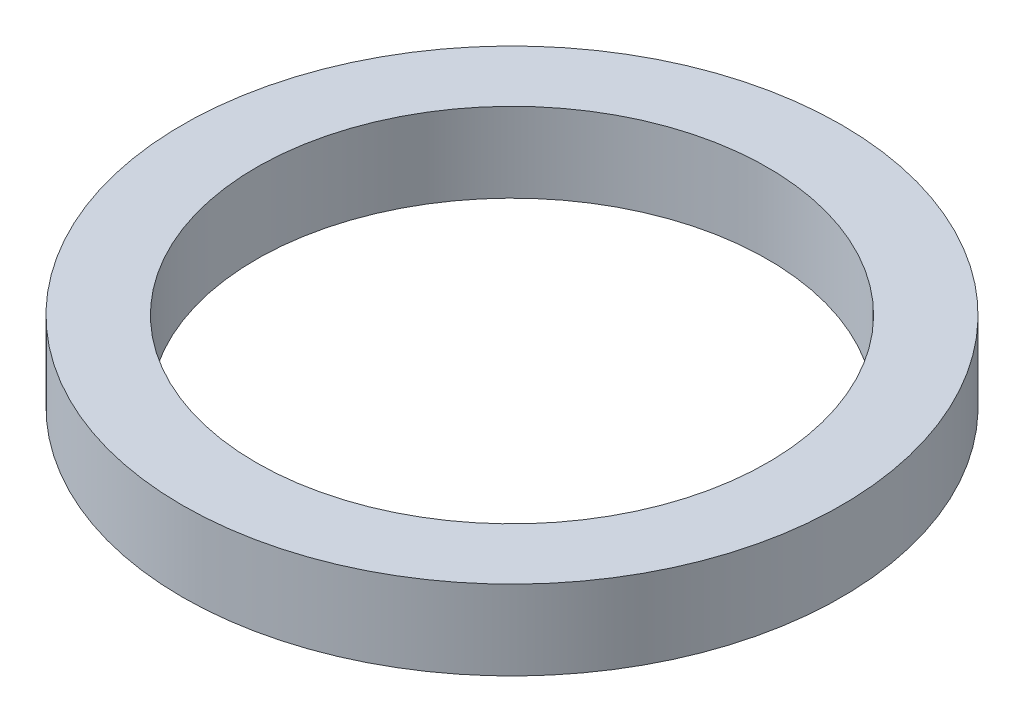
SolidWorks part; units mm, degrees
ref_plane "Front Plane" through (0, 0, 0) normal (0, 0, 1) x (1, 0, 0)
ref_plane "Top Plane" through (0, 0, 0) normal (0, 1, 0) x (1, 0, 0)
ref_plane "Right Plane" through (0, 0, 0) normal (1, 0, 0) x (0, 0, -1)
sketch "Sketch1" plane through (0, 0, 0) normal (0, 1, 0) x (1, 0, 0)
  circle A0 centre (0, 0) radius 22.5
  circle A1 centre (0, 0) radius 29
  dimension "D1" = 45
  dimension "D2" = 58
extrude "Boss-Extrude1" add sketch "Sketch1" along normal mid plane 7
equation "\"Nr\"= 78"
equation "\"module\"= 0.6"
equation "\"pressure_angle\"= 20.0"
equation "\"h_a\"= 0.6"
equation "\"h_f\"= 0.75"
equation "\"clr_tip_root\"= 0.15000000000000002"
equation "\"dp_r\"= 46.8"
equation "\"db_r\"= 43.97761465278051"
equation "\"fw_r\"= 22.845791438896047"
equation "\"alpha_r\"= 0.8539582918412556"
equation "\"beta_r\"= 4.015608891374819"
equation "\"bearing_ID\"= 45"
equation "\"bearing_OD\"= 58"
equation "\"bearing_height\"= 7"
equation "\"clearance_planet\"= 1.5"
equation "\"case_dist\"= 24.210783717444997"
equation "\"Motor_case_OD_max\"= 88.5"
equation "\"case_mounting_PCD\"= 81.0"
equation "\"bearing mount thickness\"= IIF((\"bearing_OD\" + \"output_mounting_hole_dia\" * 4) > (\"Nr\" * \"module\" + 2 * \"h_b\"), \"output_mounting_hole_dia\" * 2, ((\"Nr\" * \"module\" + 2 * \"h_b\" - (\"bearing_OD\" + \"output_mounting_hole_dia\" * 4)) / 2) + \"output_mounting_hole_dia\" * 2 + \"standard_clearance_1_5mm\")"
equation "\"case_mounting_hole_dia\"= 3"
equation "\"output_mounting_PCD\"= 66"
equation "\"output_mounting_hole_dia\"= 4"
equation "\"clearance_case_mount_holes_shell_thickness\"= 1"
equation "\"motor_case_OD_base\"= 79.0"
equation "\"sec_carrier_thickness\"= 5"
equation "\"sun_coupler_hub_thickness\"= 4"
equation "\"clearance_sun_coupler_sec_carrier\"= 1.5"
equation "\"clearance_motor_and_case\"= 5"
equation "\"motor_OD\"= 64"
equation "\"Motor_case_thickness\"= 2.5"
equation "\"Motor_case_ID\"= 74"
equation "\"case_mounting_hole_shift\"= 1.0"
equation "\"output_mounting_nut_wrench_size\"= 7"
equation "\"output_mounting_nut_thickness\"= 3.2"
equation "\"case_mounting_hole_allen_socket_dia\"= 5.5"
equation "\"output_mounting_nut_depth\"= 3"
equation "\"case_mounting_bolt_depth\"= 4.5"
equation "\"Ns\"= 24"
equation "\"ring_radial_thickness\"= 7.100000000000001"
equation "\"ring_OD\"= 61.0"
equation "\"ring_to_chamfer_clearance\"= 0.5"
equation "\"Motor_case_OD_base_to_chamfer\"= 5"
equation "\"pattern_offset_from_motor_case_OD_base\"= 3"
equation "\"pattern_bulge_dia\"= 3"
equation "\"pattern_num_bulge\"= 18"
equation "\"pattern_depth\"= 2"
equation "\"motor_height\"= 75"
equation "\"case_mounting_wrench_size\"= 5.5"
equation "\"case_mounting_nut_clearance\"= 2"
equation "\"base_plate_thickness\"= 4"
equation "\"case_mounting_nut_thickness\"= 2.4"
equation "\"case_mounting_surface_height\"= 4"
equation "\"motor_mount_hole_PCD\"= 44"
equation "\"motor_mount_hole_dia\"= 4"
equation "\"motor_mount_hole_num\"= 4"
equation "\"central_hole_offset_from_motor_mount_PCD\"= 5"
equation "\"wire_slot_dist_from_center\"= 22"
equation "\"wire_slot_length\"= 8"
equation "\"wire_slot_radius\"= 2"
equation "\"driver_upper_holes_dist_from_center\"= 29"
equation "\"driver_lower_holes_dist_from_center\"= 13"
equation "\"driver_side_holes_dist_from_center\"= 22.5"
equation "\"driver_mount_holes_dia\"= 3"
equation "\"driver_mount_inserts_OD\"= 4.8"
equation "\"driver_mount_thickness\"= 1.5"
equation "\"driver_mount_height\"= 6"
equation "\"air_flow_hole_offset\"= 3"
equation "\"num_planet\"= 3"
equation "\"planet_pin_bolt_dia\"= 2.5"
equation "\"planet_pin_socket_head_dia\"= 4.5"
equation "\"carrier_PCD\"= 34.199999999999996"
equation "\"planet_shaft_dia\"= 5"
equation "\"planet_shaft_step_offset\"= 0.8"
equation "\"carrier_trapezoidal_support_sun_offset\"= 5"
equation "\"carrier_trapezoidal_support_hole_PCD_offset_bearing_ID\"= 4"
equation "\"carrier_trapezoidal_support_hole_dia\"= 3"
equation "\"carrier_trapezoidal_support_hole_socket_head_dia\"= 5.5"
equation "\"carrier_bearing_step_width\"= 1.5"
equation "\"standard_clearance_1_5mm\"= 1.5"
equation "\"standard_fillet_1_5mm\"= 1.5"
equation "\"sun_shaft_bearing_OD\"= 14"
equation "\"sun_shaft_bearing_width\"= 5"
equation "\"standard_bearing_insertion_chamfer\"= 0.5"
equation "\"D1@Sketch1\"=\"bearing_ID\""
equation "\"D2@Sketch1\"=\"bearing_OD\""
equation "\"D1@Boss-Extrude1\"=\"bearing_height\""
equation "\"carrier_trapezoidal_support_hole_wrench_size\"= 5.5"
equation "\"planet_pin_bolt_wrench_size\"= 5"
equation "\"Np_b\"= 33"
equation "\"pressure angle\"= 20.0"
equation "\"h_b\"= 0.75"
equation "\"dp_s\"= 14.399999999999999"
equation "\"db_s\"= 13.53157373931708"
equation "\"fw_s_calc\"= 16.210783717444997"
equation "\"alpha_s\"= 0.8539582918412343"
equation "\"beta_s\"= 5.792083416317531"
equation "\"dp_p_b\"= 19.8"
equation "\"db_p_b\"= 18.605913891560988"
equation "\"fw_p_s\"= 24.345791438896047"
equation "\"alpha_p_b\"= 0.8539582918412414"
equation "\"beta_p_b\"= 3.7466288708629714"
equation "\"planet_bearing_OD\"= 8"
equation "\"planet_bearing_width\"= 2.5"
equation "\"planet_bore\"= 6"
equation "\"motor_output_hole_PCD\"= 32"
equation "\"motor_output_hole_dia\"= 4"
equation "\"motor_output_hole_num\"= 4"
equation "\"sun_shaft_bearing_ID\"= 7"
equation "\"sun_hub_dia\"= 42.0"
equation "\"sun_central_bolt_dia\"= 3"
equation "\"sun_central_bolt_socket_head_dia\"= 5.5"
equation "\"fw_s_used\"= 48.55657515634104"
equation "\"motor_output_hole_CSK_OD\"= 8"
equation "\"motor_output_hole_CSK_head_height\"= 2.0"
equation "\"bearing_retainer_thickness\"= 2"
equation "\"Np_s\"= 21"
equation "\"fw_p_b\"= 16.210783717444997"
equation "\"dp_p_s\"= 12.6"
equation "\"db_p_s\"= 11.840127021902445"
equation "\"alpha_p_s\"= 0.8539582918412556"
equation "\"beta_p_s\"= 6.86351198774606"
